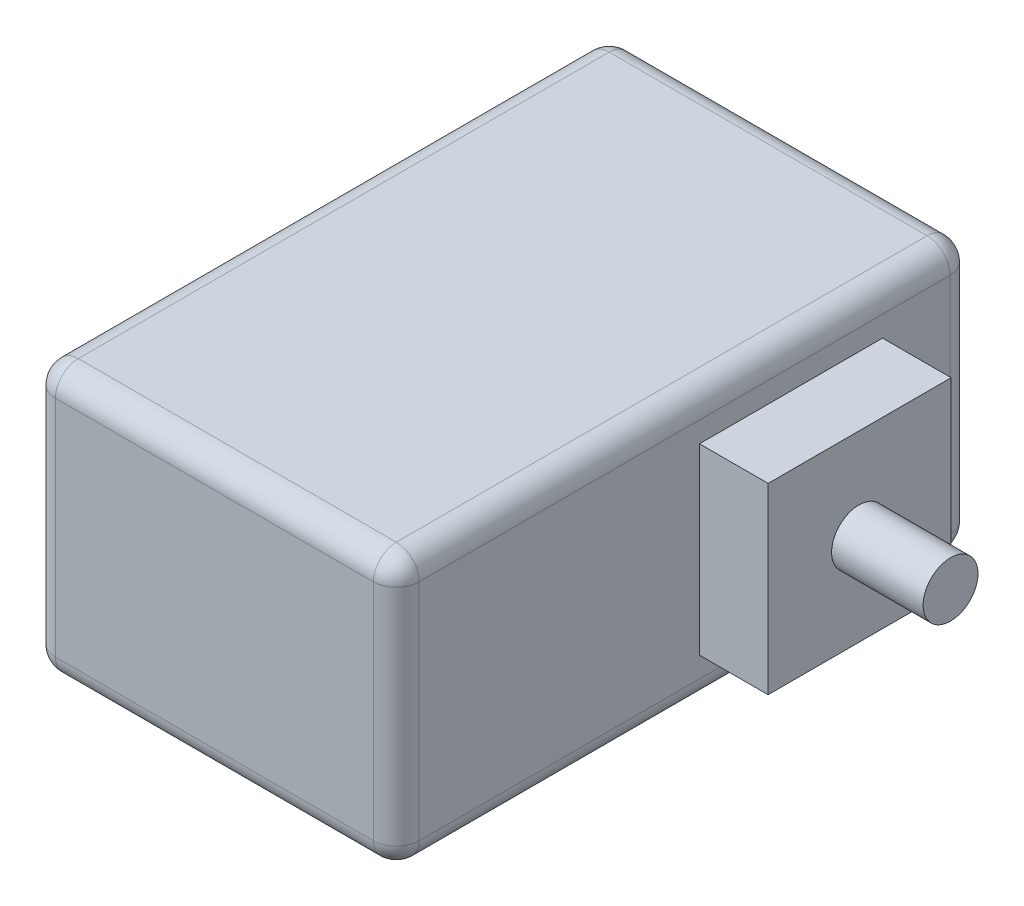
SolidWorks part; units mm, degrees
ref_plane "Front Plane" through (0, 0, 0) normal (0, 0, 1) x (1, 0, 0)
ref_plane "Top Plane" through (0, 0, 0) normal (0, 1, 0) x (1, 0, 0)
ref_plane "Right Plane" through (0, 0, 0) normal (1, 0, 0) x (0, 0, -1)
sketch "Sketch1" plane through (0, 0, 0) normal (0, 0, 1) x (1, 0, 0)
  line L1 (-79.5, -59) -> (79.5, -59)
  line L2 (-79.5, -59) -> (-79.5, 59)
  line L3 (-79.5, 59) -> (79.5, 59)
  line L4 (79.5, -59) -> (79.5, 59)
  line L5 (-79.5, -59) -> (79.5, 59) construction
  line L6 (-79.5, 59) -> (79.5, -59) construction
  point P0 (0, 0)
  dimension "D1" = 159
  dimension "D2" = 118
extrude "Boss-Extrude1" add sketch "Sketch1" along normal mid plane 252
fillet "Fillet1" radius 10 12 edges at (-79.5, 0, -126) (0, -59, -126) (0, -59, 126) (0, 59, 126) (0, 59, -126) (-79.5, 0, 126) (79.5, 0, 126) (79.5, 0, -126) (79.5, -59, 0) (79.5, 59, 0) (-79.5, -59, 0) (-79.5, 59, 0)
sketch "Sketch2" [suppressed] plane through (0, 0, 0) normal (1, 0, 0) x (0, 0, -1)
  line L0 (126, 0) -> (126, 46.1196)
  line L1 (126, 39) -> (126, -39) construction
  line L2 (165, 70) -> (101.975, 70)
  line L3 (165, 70) -> (165, 0)
  line L4 (165, 0) -> (126, 0)
  spline S0 degree 2 poles (126, 46.1196) (67.0519, 32.7489) (101.975, 70) knots 0 0 0 1 1 1
  dimension "D1" = 70
  dimension "D2" = 39
revolve "Revolve1" [suppressed] add sketch "Sketch2" angle 360 about L4
sketch "Sketch3" [suppressed] plane through (0, 0, -111.5) normal (0, 0, -1) x (-1, 0, 0)
  circle A0 centre (0, 0) radius 52.6471
extrude "Cut-Extrude1" [suppressed] cut sketch "Sketch3" against normal blind 10
sketch "Sketch4" [suppressed] plane through (0, 0, -101.5) normal (0, 0, -1) x (-1, 0, 0)
  circle A0 centre (0, 0) radius 10
  dimension "D1" = 20
extrude "Cut-Extrude2" [suppressed] cut sketch "Sketch4" against normal blind 20
sketch "Sketch5" [suppressed] plane through (0, 0, 126) normal (0, 0, 1) x (1, 0, 0)
  line L0 (-73.5, 59) -> (73.5, 59) construction
  circle A0 centre (37.6213, 4) radius 6.5
  dimension "D1" = 13
  dimension "D2" = 55
extrude "Cut-Extrude3" [suppressed] cut sketch "Sketch5" against normal blind 10
pattern_linear "LPattern1" [suppressed] count 2 spacing 55
sketch "Sketch6" plane through (79.5, 0, 0) normal (1, 0, 0) x (0, 0, -1)
  line L0 (116, -59) -> (-116, -59) construction
  line L1 (6.5, -40) -> (86.5, -40)
  line L2 (6.5, -40) -> (6.5, 40)
  line L3 (6.5, 40) -> (86.5, 40)
  line L4 (86.5, -40) -> (86.5, 40)
  line L5 (6.5, -40) -> (86.5, 40) construction
  line L6 (6.5, 40) -> (86.5, -40) construction
  line L7 (126, 49) -> (126, -49) construction
  point P0 (46.5, 0)
  dimension "D1" = 59
  dimension "D2" = 80
  dimension "D3" = 80
  dimension "D4" = 79.5
extrude "Boss-Extrude2" add sketch "Sketch6" along normal blind 30
sketch "Sketch7" plane through (109.5, 0, 0) normal (1, 0, 0) x (0, 0, -1)
  circle A0 centre (46.2384, 0) radius 12
  dimension "D1" = 24
extrude "Boss-Extrude3" add sketch "Sketch7" along normal blind 40
sketch "Sketch8" plane through (0, 0, 126) normal (0, 0, 1) x (1, 0, 0)
  line L0 (55.8126, -59) -> (79.5, -59)
  line L1 (69.5, -59) -> (-69.5, -59) construction
  line L2 (79.5, -59) -> (79.5, -77)
  line L3 (79.5, -77) -> (103.5, -77)
  line L4 (79.5, 49) -> (79.5, -49) construction
  line L5 (109.5, 40) -> (109.5, -40) construction
  dimension "D1" = 18
  dimension "D2" = 6
extrude "Extrude-Thin1" [suppressed] add sketch "Sketch8" against normal blind 250 thin
sketch "Sketch10" plane through (0, 0, 0) normal (0, 0, 1) x (1, 0, 0)
  line L6 (-36.6766, -59) -> (-55.5, -59)
  line L7 (-55.5, -59) -> (-55.5, -77)
  line L8 (-55.5, -77) -> (-79.5, -77)
extrude "Extrude-Thin2" [suppressed] add sketch "Sketch10" along normal through all and the other way through all thin
sketch "Sketch11" plane through (-79.5, 0, 0) normal (-1, 0, 0) x (0, 0, 1)
  line L0 (116, -59) -> (-116, -59) construction
  circle A0 centre (93.0823, 26.75) radius 8.5
  circle A1 centre (93.0823, -26.75) radius 10.5
  dimension "D2" = 17
  dimension "D3" = 21
  dimension "D4" = 32.25
  dimension "D1" = 53.5
extrude "Cut-Extrude5" cut sketch "Sketch11" against normal blind 50
sketch "Sketch12" plane through (0, -59, 0) normal (0, -1, 0) x (1, 0, 0)
  line L0 (69.5, -126) -> (-69.5, -126) construction
  line L1 (-79.5, -116) -> (-79.5, 116) construction
  circle A0 centre (-38.5, -84) radius 7.9406
  circle A1 centre (56.5, -84) radius 7.9406
  circle A2 centre (56.5, -9) radius 7.9406
  circle A3 centre (-38.5, -9) radius 7.9406
  dimension "D1" = 95
  dimension "D2" = 75
  dimension "D3" = 42
  dimension "D4" = 41
extrude "Cut-Extrude6" cut sketch "Sketch12" against normal blind 10
